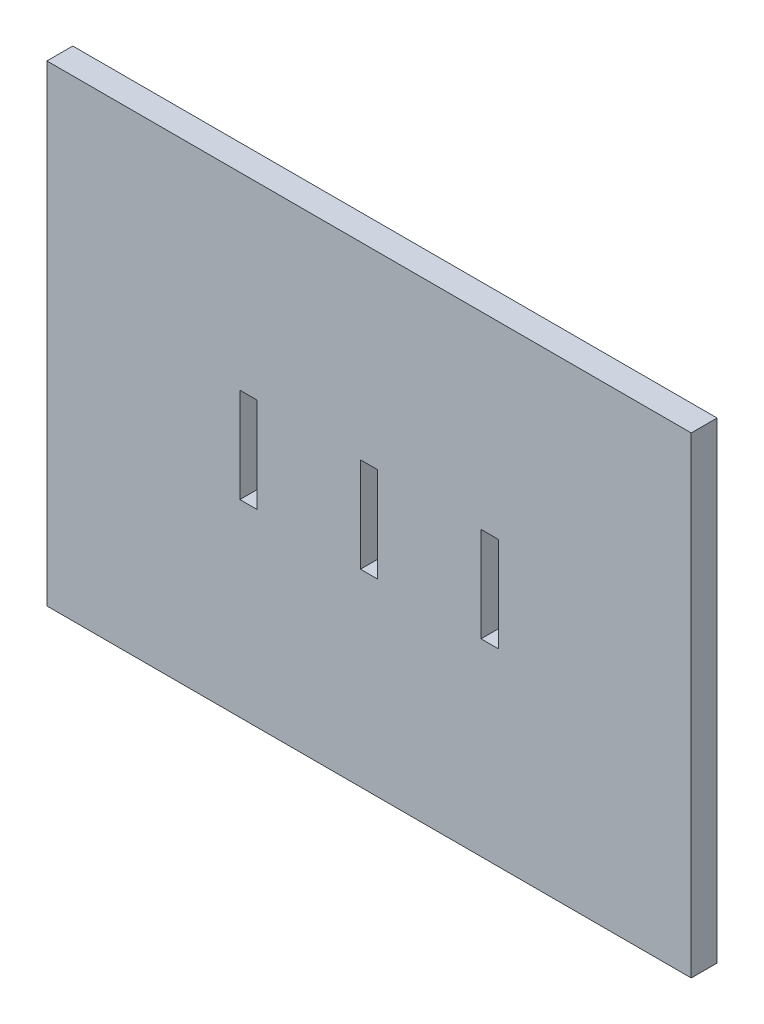
SolidWorks part; units mm, degrees
ref_plane "Front Plane" through (0, 0, 0) normal (1, 0, 0) x (0, 1, 0)
ref_plane "Top Plane" through (0, 0, 0) normal (0, 0, 1) x (0, 1, 0)
ref_plane "Right Plane" through (0, 0, 0) normal (0, 1, 0) x (-1, 0, 0)
sketch "Sketch1" plane through (0, 0, 0) normal (0, 0, 1) x (0, 1, 0)
  line L0 (-6.5, -9.6) -> (6.5, -9.6) construction
  line L1 (-6.5, -9.6) -> (-6.5, 9.6) construction
  line L2 (-6.5, 9.6) -> (6.5, 9.6) construction
  line L3 (6.5, -9.6) -> (6.5, 9.6) construction
  line L4 (-6.5, -9.6) -> (6.5, 9.6) construction
  line L5 (-6.5, 9.6) -> (6.5, -9.6) construction
  line L6 (-15, -20) -> (15, -20) construction
  line L7 (-15, -20) -> (-15, 20) construction
  line L8 (-15, 20) -> (15, 20) construction
  line L9 (15, -20) -> (15, 20) construction
  line L10 (-15, -20) -> (15, 20) construction
  line L11 (-15, 20) -> (15, -20) construction
  line L12 (-13.7, 18.7) -> (13.7, 18.7)
  line L13 (13.7, -18.7) -> (13.7, 18.7)
  line L14 (-13.7, -18.7) -> (13.7, -18.7)
  line L15 (-13.7, -18.7) -> (-13.7, 18.7)
  line L16 (0, 0) -> (-13.7, 0) construction
  line L17 (0, 7) -> (-13.7, 7) construction
  line L18 (0, -7) -> (-13.7, -7) construction
  line L19 (-2.75, 7.5) -> (2.75, 7.5)
  line L20 (-2.75, -0.5) -> (2.75, -0.5)
  line L21 (-2.75, -0.5) -> (-2.75, 0.5)
  line L22 (-2.75, 0.5) -> (2.75, 0.5)
  line L23 (2.75, -0.5) -> (2.75, 0.5)
  line L24 (-2.75, -0.5) -> (2.75, 0.5) construction
  line L25 (-2.75, 0.5) -> (2.75, -0.5) construction
  line L26 (2.75, 6.5) -> (2.75, 7.5)
  line L27 (-2.75, 6.5) -> (2.75, 6.5)
  line L28 (-2.75, 6.5) -> (-2.75, 7.5)
  line L29 (-2.75, 0.5) -> (2.75, 0.5)
  line L30 (2.75, -0.5) -> (2.75, 0.5)
  line L31 (-2.75, -0.5) -> (2.75, -0.5)
  line L32 (-2.75, -0.5) -> (-2.75, 0.5)
  line L33 (-2.75, -6.5) -> (2.75, -6.5)
  line L34 (2.75, -7.5) -> (2.75, -6.5)
  line L35 (-2.75, -7.5) -> (2.75, -7.5)
  line L36 (-2.75, -7.5) -> (-2.75, -6.5)
  point P0 (0, 0)
  point P5 (0, 0)
  dimension "D1" = 13
  dimension "D2" = 19.2
  dimension "D3" = 30
  dimension "D4" = 40
  dimension "D8" = 5.5
  dimension "D9" = 1
  dimension "D5" = 1.3
  dimension "D6" = 7
  dimension "D7" = 7
  dimension "D10" = 2
extrude "Boss-Extrude1" add sketch "Sketch1" along normal blind 1.5 contours L15 L14 L13 L12 L23 L20 L21 L22 L27 L28 L19 L26 L35 L36 L33 L34
